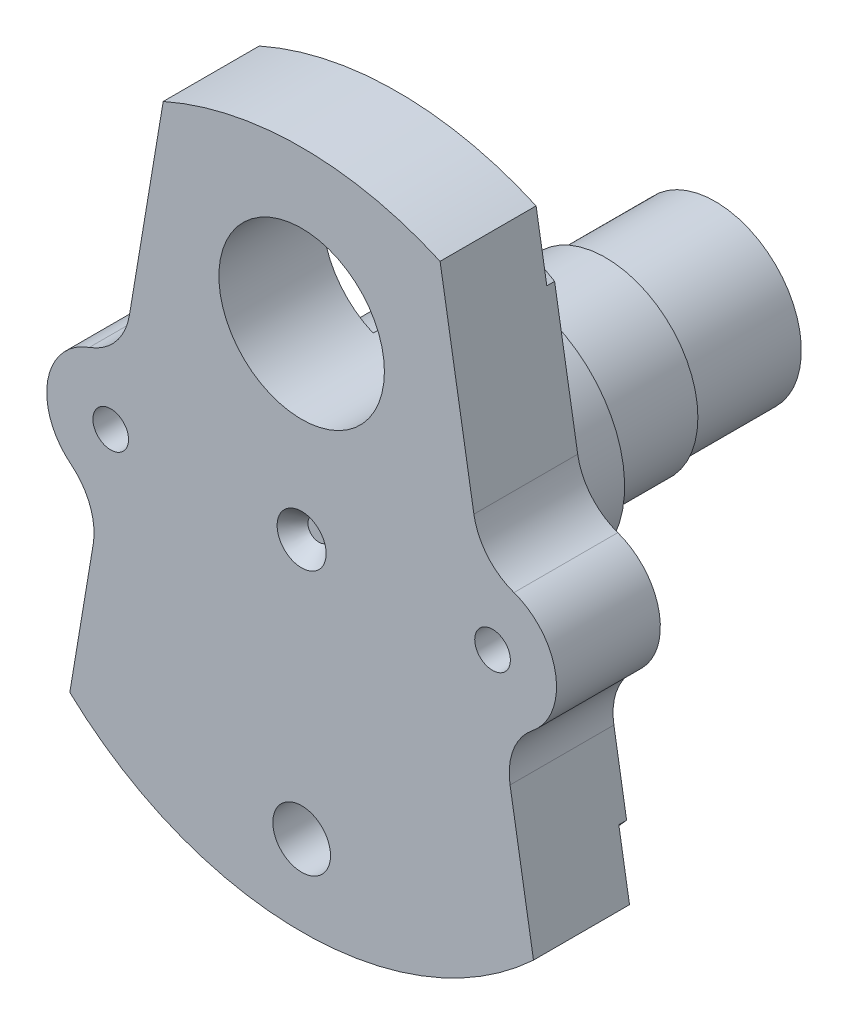
SolidWorks part; units mm, degrees
ref_plane "Front Plane" through (0, 0, 0) normal (0, 0, 1) x (1, 0, 0)
ref_plane "Top Plane" through (0, 0, 0) normal (0, 1, 0) x (1, 0, 0)
ref_plane "Right Plane" through (0, 0, 0) normal (1, 0, 0) x (0, 0, -1)
sketch "Sketch1" plane through (0, 0, 0) normal (0, 0, 1) x (1, 0, 0)
  line L0 (36.1365, -18.7745) -> (40.1958, -43.0492)
  line L1 (24.0031, 53.7846) -> (29.8621, 18.7473)
  line L7 (-24.0031, 53.7846) -> (-29.8621, 18.7473)
  line L10 (-36.1365, -18.7745) -> (-40.1958, -43.0492)
  arc A0 (-40.1958, -43.0492) -> (40.1958, -43.0492) centre (0, 0) ccw
  circle A2 centre (-33.1, 0) radius 3.0908
  circle A3 centre (33.1, 0) radius 3.0908
  arc A5 (-36.8149, 10.45) -> (-40.0101, -8.6749) centre (-33.1, 0) ccw
  arc A6 (40.0101, -8.6749) -> (36.1365, -18.7745) centre (46.6541, -17.0157) ccw
  arc A7 (-36.8149, 10.45) -> (-29.8621, 18.7473) centre (-40.3904, 20.5078) ccw
  arc A8 (-40.0101, -8.6749) -> (-36.1365, -18.7745) centre (-46.6541, -17.0157) cw
  arc A9 (36.8149, 10.45) -> (40.0101, -8.6749) centre (33.1, 0) cw
  arc A10 (36.8149, 10.45) -> (29.8621, 18.7473) centre (40.3904, 20.5078) cw
  arc A11 (24.0031, 53.7846) -> (-24.0031, 53.7846) centre (0, 0) ccw
  circle A12 centre (0, 32.4) radius 14.35
  circle A13 centre (0.0044, -44.95) radius 5
extrude "Boss-Extrude1" add sketch "Sketch1" against normal blind 18
sketch "Sketch2" plane through (0, 0, -18) normal (0, 0, -1) x (-1, 0, 0)
  circle A0 centre (0, 0) radius 20
extrude "Boss-Extrude2" add sketch "Sketch2" along normal blind 18
sketch "Sketch3" plane through (0, 0, -36) normal (0, 0, -1) x (-1, 0, 0)
  circle A0 centre (0, 0) radius 16
extrude "Boss-Extrude3" add sketch "Sketch3" along normal blind 35.7
sketch "Sketch5" plane through (0, 0, -71.7) normal (0, 0, -1) x (-1, 0, 0)
  circle A0 centre (0, 0) radius 14.935
extrude "Cut-Extrude1" cut sketch "Sketch5" against normal blind 19 flip side to cut
sketch "Sketch6" plane through (0, 0, 0) normal (0, 0, 1) x (1, 0, 0)
  line L0 (0, 32.4) -> (0, 0) construction
  circle A0 centre (0, 32.4) radius 14.35
extrude "Cut-Extrude2" cut sketch "Sketch6" against normal blind 22.35
sketch "Sketch7" plane through (0, 0, 0) normal (0, 0, 1) x (1, 0, 0)
  circle A0 centre (0, 0) radius 4.25
extrude "Cut-Extrude3" cut sketch "Sketch7" against normal blind 3 draft 38
sketch "Sketch9" plane through (0, 0, -18) normal (0, 0, -1) x (-1, 0, 0)
  circle A0 centre (0, 0) radius 49.9231
extrude "Cut-Extrude4" cut sketch "Sketch9" against normal blind 1.35 flip side to cut
